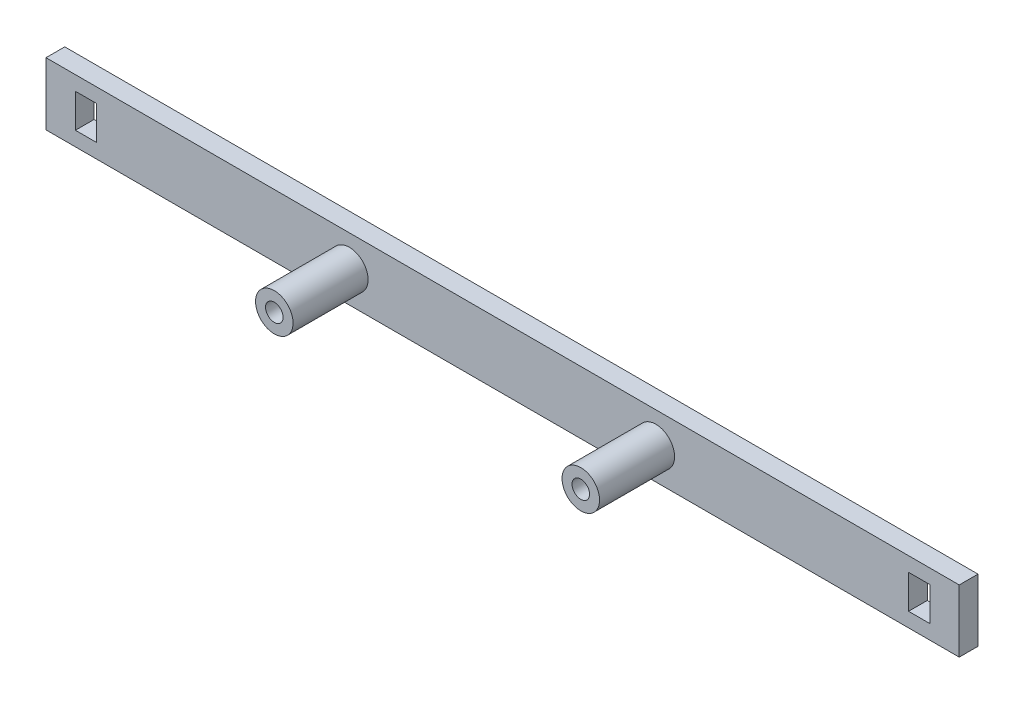
SolidWorks part; units mm, degrees
ref_plane "前视基准面" through (0, 0, 0) normal (0, 0, 1) x (1, 0, 0)
ref_plane "上视基准面" through (0, 0, 0) normal (0, 1, 0) x (1, 0, 0)
ref_plane "右视基准面" through (0, 0, 0) normal (1, 0, 0) x (0, 0, -1)
other "Configuration Table"
sketch "草图1" plane through (0, 0, 0) normal (0, 0, 1) x (1, 0, 0)
  line L1 (-73, -5) -> (73, -5)
  line L2 (-73, -5) -> (-73, 5)
  line L3 (-73, 5) -> (73, 5)
  line L4 (73, -5) -> (73, 5)
  dimension "D1" = 73
  dimension "D2" = 73
  dimension "D3" = 5
  dimension "D4" = 5
extrude "主板轻量横条146x10" add sketch "草图1" along normal blind 3
sketch "草图2" plane through (0, 0, 0) normal (0, 0, 1) x (1, 0, 0)
  circle A0 centre (-24.5, 0) radius 3
  circle A1 centre (24.5, 0) radius 3
  dimension "D1" = 6
  dimension "D2" = 24.5
  dimension "D3" = 24.5
extrude "主板12mm支柱" add sketch "草图2" along normal blind 12 from offset 3
sketch "草图3" plane through (0, 0, 0) normal (0, 0, 1) x (1, 0, 0)
  circle A0 centre (-24.5, 0) radius 1.4
  circle A1 centre (24.5, 0) radius 1.4
  dimension "D1" = 2.8
  dimension "D2" = 24.5
  dimension "D3" = 24.5
extrude "主板M2p5通孔" cut sketch "草图3" against normal through all and the other way through all
sketch "草图4" plane through (0, 0, 0) normal (0, 0, 1) x (1, 0, 0)
  line L1 (-68.3, -2.7) -> (-64.9, -2.7)
  line L2 (-68.3, -2.7) -> (-68.3, 2.7)
  line L3 (-68.3, 2.7) -> (-64.9, 2.7)
  line L4 (-64.9, -2.7) -> (-64.9, 2.7)
  line L6 (64.9, -2.7) -> (68.3, -2.7)
  line L7 (64.9, -2.7) -> (64.9, 2.7)
  line L8 (64.9, 2.7) -> (68.3, 2.7)
  line L9 (68.3, -2.7) -> (68.3, 2.7)
  dimension "D1" = 64.9
  dimension "D2" = 68.3
  dimension "D3" = 64.9
  dimension "D4" = 2.7
  dimension "D5" = 2.7
extrude "梁上M3调节槽" cut sketch "草图4" against normal through all and the other way through all
